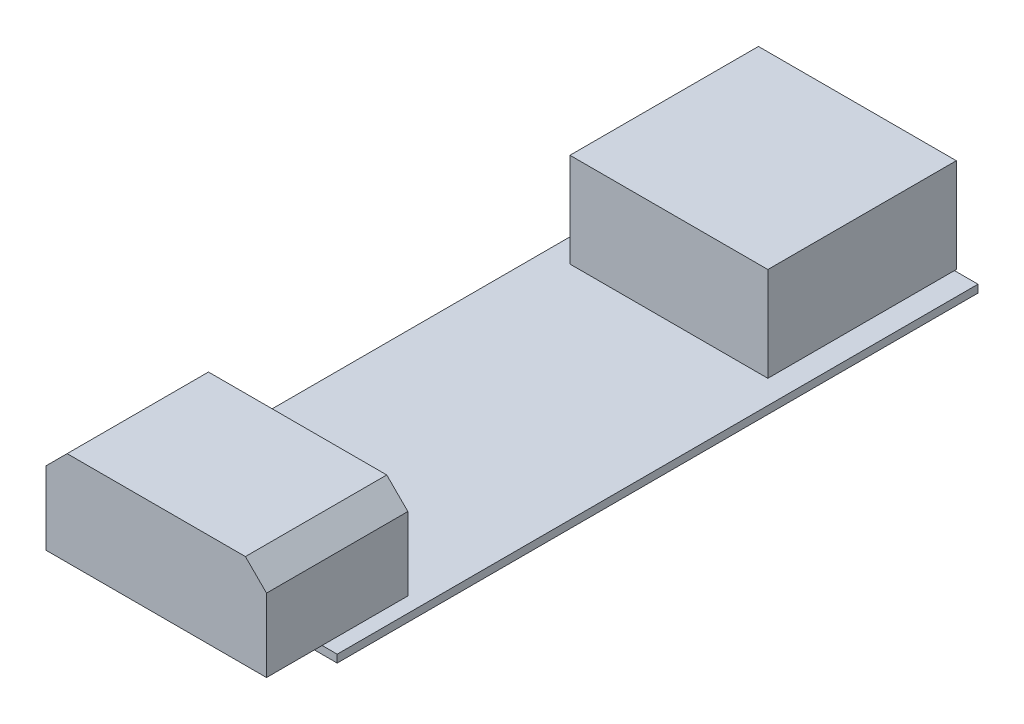
SolidWorks part; units mm, degrees
ref_plane "Płaszczyzna przednia" through (0, 0, 0) normal (0, 0, 1) x (1, 0, 0)
ref_plane "Płaszczyzna górna" through (0, 0, 0) normal (0, 1, 0) x (1, 0, 0)
ref_plane "Płaszczyzna prawa" through (0, 0, 0) normal (1, 0, 0) x (0, 0, -1)
sketch "Szkic1" plane through (0, 0, 0) normal (0, 0, 1) x (1, 0, 0)
  line L0 (10.58, 5) -> (11.7, 3.88)
  line L1 (0, 0) -> (11.7, 0)
  line L2 (0, 0) -> (0, 3.88)
  line L3 (1.12, 5) -> (10.58, 5)
  line L4 (11.7, 0) -> (11.7, 3.88)
  line L5 (0, 3.88) -> (1.12, 5)
  point P1 (11.7, 5)
  point P2 (0, 5)
  dimension "D1" = 11.7
  dimension "D2" = 5
extrude "Dodanie-wyciągnięcie1" add sketch "Szkic1" along normal blind 7.5
sketch "Szkic2" plane through (0, 0, 0) normal (0, -1, 0) x (1, 0, 0)
  line L0 (0, 7.5) -> (11.7, 7.5) construction
  line L1 (-0.5, 4.55) -> (12.5, 4.55)
  line L2 (-0.5, 4.55) -> (-0.5, -29.45)
  line L3 (-0.5, -29.45) -> (12.5, -29.45)
  line L4 (12.5, 4.55) -> (12.5, -29.45)
  line L5 (0, 7.5) -> (0, 0) construction
  dimension "D1" = 2.95
  dimension "D2" = 13
  dimension "D3" = 34
  dimension "D4" = 0.5
extrude "Dodanie-wyciągnięcie2" add sketch "Szkic2" along normal blind 0.41
sketch "Szkic3" plane through (0, -0.41, 0) normal (0, -1, 0) x (1, 0, 0)
  line L0 (11.7, 4.55) -> (0, 4.55) construction
  circle A0 centre (2.2553, 0.3) radius 0.3
  circle A1 centre (4.7553, 0.3) radius 0.3
  circle A2 centre (7.2553, 0.3) radius 0.3
  circle A3 centre (9.7553, 0.3) radius 0.3
  dimension "D3" = 0.6
  dimension "D1" = 4.25
  dimension "D2" = 4
extrude "Dodanie-wyciągnięcie3" add sketch "Szkic3" along normal blind 1.69
sketch "Szkic4" plane through (0, 0, 0) normal (0, 1, 0) x (1, 0, 0)
  line L0 (-0.5, 29.45) -> (12.5, 29.45) construction
  line L1 (0.75, 29.55) -> (11.25, 29.55)
  line L2 (0.75, 29.55) -> (0.75, 19.55)
  line L3 (0.75, 19.55) -> (11.25, 19.55)
  line L4 (11.25, 29.55) -> (11.25, 19.55)
  line L5 (-0.5, -4.55) -> (-0.5, 29.45) construction
  dimension "D1" = 10.5
  dimension "D2" = 10
  dimension "D3" = 0.1
  dimension "D4" = 1.25
extrude "Dodanie-wyciągnięcie4" add sketch "Szkic4" along normal blind 5
sketch "Szkic6" plane through (0, -0.41, 0) normal (0, -1, 0) x (1, 0, 0)
  line L0 (-0.5, -29.45) -> (12.5, -29.45) construction
  circle A0 centre (2.2553, -26.7) radius 0.4
  circle A1 centre (4.7553, -26.7) radius 0.4
  circle A2 centre (7.2553, -26.7) radius 0.4
  circle A3 centre (9.7553, -26.7) radius 0.4
  circle A4 centre (4.7553, -21.7) radius 0.4
  circle A5 centre (7.2553, -21.7) radius 0.4
  circle A6 centre (9.7553, -21.7) radius 0.4
  circle A7 centre (2.2553, -21.7) radius 0.4
  dimension "D1" = 0.8
  dimension "D2" = 2.75
  dimension "D3" = 4
  dimension "D4" = 2
extrude "Dodanie-wyciągnięcie5" add sketch "Szkic6" along normal blind 1.7
